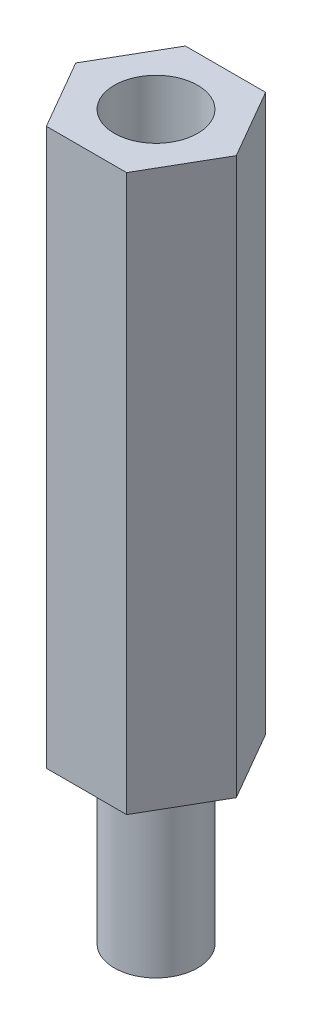
SolidWorks part; units mm, degrees
material "Latón"
ref_plane "Alzado" through (0, 0, 0) normal (0, 0, 1) x (1, 0, 0)
ref_plane "Planta" through (0, 0, 0) normal (0, 1, 0) x (1, 0, 0)
ref_plane "Vista lateral" through (0, 0, 0) normal (1, 0, 0) x (0, 0, -1)
sketch "Croquis1" plane through (0, 0, 0) normal (0, 1, 0) x (1, 0, 0)
  line L1 (1.4434, -2.5) -> (2.8868, 0)
  line L2 (2.8868, 0) -> (1.4434, 2.5)
  line L3 (1.4434, 2.5) -> (-1.4434, 2.5)
  line L4 (-1.4434, 2.5) -> (-2.8868, 0)
  line L5 (-2.8868, 0) -> (-1.4434, -2.5)
  line L6 (-1.4434, -2.5) -> (1.4434, -2.5)
  circle A0 centre (0, 0) radius 2.5 construction
  circle A1 centre (0, 0) radius 1.5
  dimension "D2" = 3
  dimension "D1" = 5
extrude "Saliente-Extruir1" add sketch "Croquis1" along normal blind 20
sketch "Croquis2" plane through (0, 0, 0) normal (0, -1, 0) x (1, 0, 0)
  circle A0 centre (0, 0) radius 1.5 construction
  circle A1 centre (0, 0) radius 1.5
extrude "Saliente-Extruir2" add sketch "Croquis2" along normal blind 6 separate body
sketch "Sketch1" plane through (0, 20, 0) normal (0, 1, 0) x (1, 0, 0)
  circle A0 centre (0, 0) radius 2.8868
